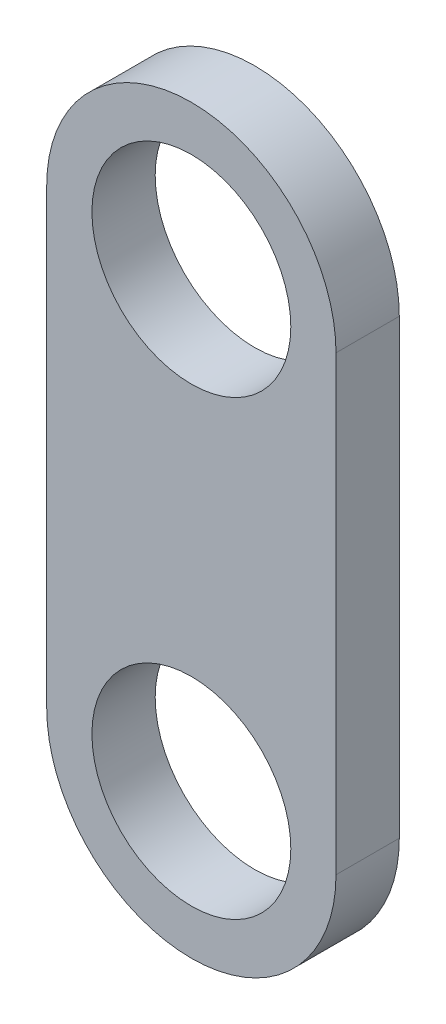
SolidWorks part; units mm, degrees
ref_plane "Front Plane" through (0, 0, 0) normal (0, 0, 1) x (1, 0, 0)
ref_plane "Top Plane" through (0, 0, 0) normal (0, 1, 0) x (1, 0, 0)
ref_plane "Right Plane" through (0, 0, 0) normal (1, 0, 0) x (0, 0, -1)
sketch "Sketch1" plane through (0, 0, 0) normal (0, 0, 1) x (1, 0, 0)
  line L0 (0, 25) -> (0, -25) construction
  line L1 (0, -55) -> (0, 55) construction
  line L2 (55, 0) -> (-55, 0) construction
  line L3 (-16, 25) -> (-16, -25)
  line L4 (16, -25) -> (16, 25)
  circle A0 centre (0, 25) radius 11
  circle A1 centre (0, -25) radius 11
  circle A2 centre (0, 25) radius 16
  circle A3 centre (0, -25) radius 16
  point P5 (0, 0)
  dimension "D2" = 22
  dimension "D1" = 50
  dimension "D3" = 5
extrude "Boss-Extrude1" add sketch "Sketch1" along normal blind 7
